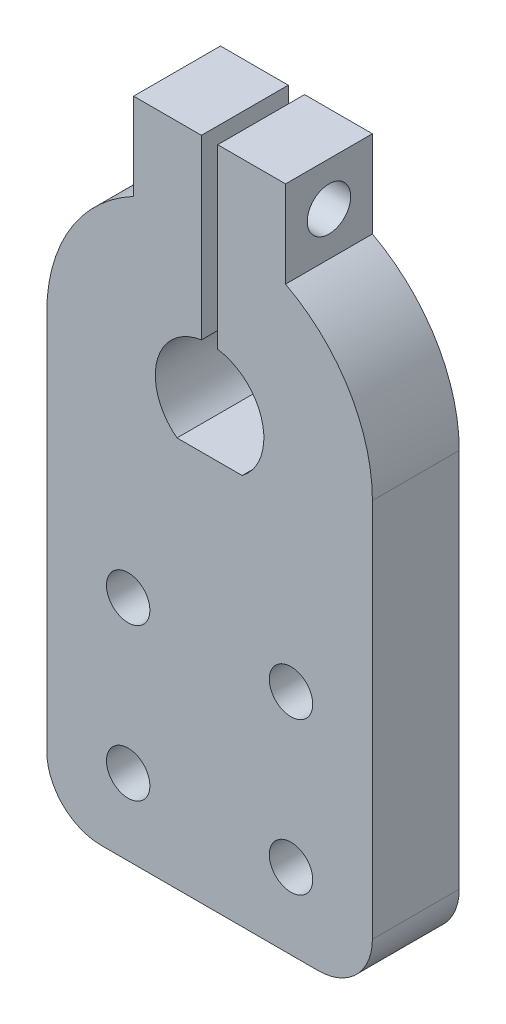
SolidWorks part; units mm, degrees
material "6061 合金"
ref_plane "前视基准面" through (0, 0, 0) normal (0, 0, 1) x (1, 0, 0)
ref_plane "上视基准面" through (0, 0, 0) normal (0, 1, 0) x (1, 0, 0)
ref_plane "右视基准面" through (0, 0, 0) normal (1, 0, 0) x (0, 0, -1)
sketch "草图1" plane through (0, 0, 0) normal (0, 0, 1) x (1, 0, 0)
  line L0 (-15, 0) -> (-15, -40)
  line L1 (-15, -40) -> (15, -40)
  line L2 (15, -40) -> (15, 0)
  line L3 (7, 21.2665) -> (7, 13.2665)
  line L4 (0, -55) -> (0, 55) construction
  line L5 (7, 21.2665) -> (0.75, 21.2665)
  line L6 (0.75, 21.2665) -> (0.75, 4.9434)
  line L7 (-7, 21.2665) -> (-7, 13.2665)
  line L8 (-0.75, 21.2665) -> (-0.75, 4.9434)
  line L9 (-7, 21.2665) -> (-0.75, 21.2665)
  line L11 (3, -4) -> (-3, -4)
  arc A0 (15, 0) -> (7, 13.2665) centre (0, 0) ccw
  arc A1 (-0.75, 4.9434) -> (-3, -4) centre (0, 0) ccw
  arc A2 (-7, 13.2665) -> (-15, 0) centre (0, 0) ccw
  circle A3 centre (-7.5, -19) radius 2
  circle A4 centre (-7.5, -33) radius 2
  circle A5 centre (7.5, -33) radius 2
  circle A6 centre (7.5, -19) radius 2
  arc A7 (3, -4) -> (0.75, 4.9434) centre (0, 0) ccw
  dimension "D1" = 4
  dimension "D3" = 7
  dimension "D2" = 7.5
  dimension "D4" = 14
extrude "凸台-拉伸1" add sketch "草图1" along normal blind 8
sketch "草图2" plane through (7, 0, 0) normal (1, 0, 0) x (0, 0, -1)
  line L0 (-8, 21.2665) -> (0, 21.2665) construction
  circle A0 centre (-4, 17.2665) radius 2
  dimension "D1" = 4
extrude "切除-拉伸1" cut sketch "草图2" against normal blind 15
fillet "圆角2" radius 5 2 edges at (-15, -40, 4) (15, -40, 4)
